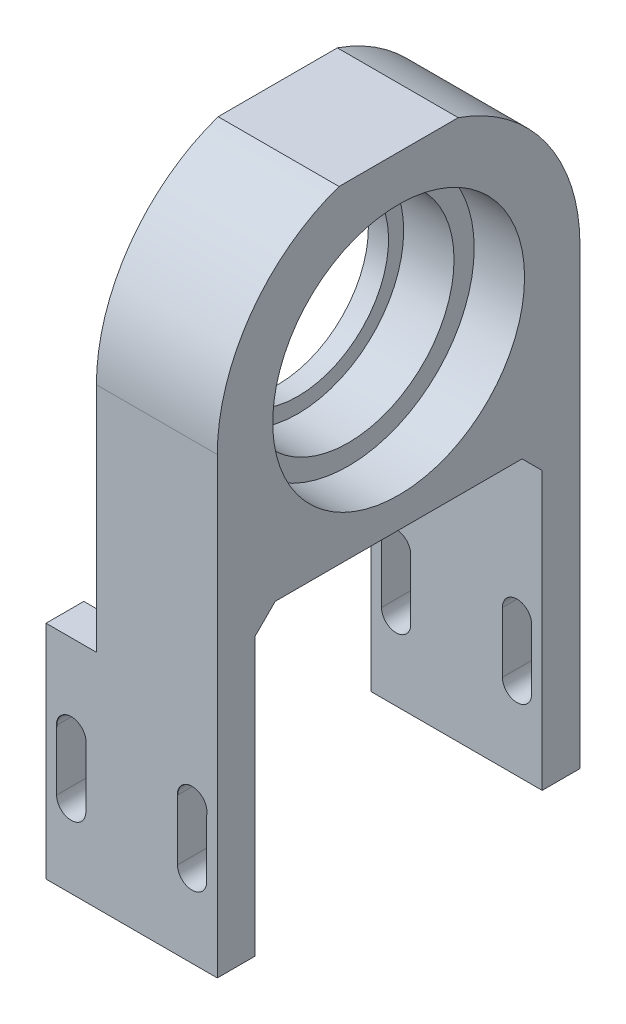
SolidWorks part; units mm, degrees
material "6061 Alloy"
ref_plane "Front Plane" through (0, 0, 0) normal (0, 0, 1) x (1, 0, 0)
ref_plane "Top Plane" through (0, 0, 0) normal (0, 1, 0) x (1, 0, 0)
ref_plane "Right Plane" through (0, 0, 0) normal (1, 0, 0) x (0, 0, -1)
sketch "Sketch1" plane through (0, 0, 0) normal (0, 0, 1) x (1, 0, 0)
  line L0 (0, 0) -> (17, 0)
  line L1 (17, 0) -> (17, 29)
  line L3 (17, 29) -> (17, 62)
  line L4 (17, 62) -> (5, 62)
  line L5 (5, 62) -> (5, 22)
  line L6 (5, 22) -> (0, 22)
  line L7 (0, 22) -> (0, 0)
  dimension "D1" = 17
  dimension "D2" = 62
  dimension "D3" = 22
  dimension "D4" = 12
extrude "Boss-Extrude1" add sketch "Sketch1" along normal blind 36
sketch "Sketch2" plane through (17, 0, 0) normal (1, 0, 0) x (0, 0, -1)
  line L0 (-18, 62) -> (-18, 12.1467) construction
  line L1 (-36, 62) -> (0, 62) construction
  circle A0 centre (-18, 45) radius 10.5
  dimension "D1" = 21
  dimension "D2" = 17
extrude "Cut-Extrude1" cut sketch "Sketch2" against normal through all
sketch "Sketch3" plane through (17, 0, 0) normal (1, 0, 0) x (0, 0, -1)
  line L0 (-36, 0) -> (0, 0) construction
  line L1 (-32.25, 0) -> (-3.75, 0)
  line L2 (-32.25, 0) -> (-32.25, 29.5)
  line L3 (-32.25, 29.5) -> (-3.75, 29.5)
  line L4 (-3.75, 0) -> (-3.75, 29.5)
  line L6 (-18, 0) -> (-18, 45) construction
  dimension "D1" = 28.5
  dimension "D2" = 29.5
extrude "Cut-Extrude2" cut sketch "Sketch3" against normal through all
chamfer "Chamfer1" distance 2 angle 45 2 edges at (11, 29.5, 32.25) (11, 29.5, 3.75)
sketch "Sketch6" plane through (5, 0, 0) normal (-1, 0, 0) x (0, 0, 1)
  circle A0 centre (18, 45) radius 10.5 construction
  circle A1 centre (18, 45) radius 10.5
  circle A2 centre (18, 45) radius 9
  dimension "D1" = 1.5
extrude "Boss-Extrude2" add sketch "Sketch6" against normal blind 2
sketch "Sketch10" plane through (5, 0, 0) normal (-1, 0, 0) x (0, 0, 1)
  circle A0 centre (18, 45) radius 11
  circle A1 centre (18, 45) radius 15
  dimension "D1" = 22
  dimension "D2" = 30
extrude "Cut-Extrude4" cut sketch "Sketch10" against normal blind 0.6
sketch "Sketch11" plane through (17, 0, 0) normal (1, 0, 0) x (0, 0, -1)
  circle A0 centre (-18, 45) radius 12.5
  dimension "D1" = 25
extrude "Cut-Extrude5" cut sketch "Sketch11" against normal blind 5
sketch "Sketch14" plane through (0, 0, 36) normal (0, 0, 1) x (1, 0, 0)
  line L0 (2.5, 13.75) -> (14.5, 13.75)
  line L3 (8.5, 13.75) -> (8.5, 0)
  line L4 (0, 0) -> (17, 0) construction
  line L5 (5, 29.5) -> (17, 29.5) construction
  point P0 (14.5, 13.75)
  point P2 (2.5, 13.75)
  dimension "D1" = 15.75
  dimension "D2" = 12
hole_wizard "M2.5 Clearance Hole1" positions "Sketch14" profile "Sketch13" hole size "M2.5" standard "DIN" end condition through all
sketch "Sketch13" plane through (14.5, 13.75, 36) normal (1, 0, 0) x (0, -1, 0)
  line L0 (0, 0) -> (0, 36)
  line L1 (0, 36) -> (1.45, 36)
  line L2 (1.45, 36) -> (1.45, 0.025)
  line L3 (1.45, 0.025) -> (1.475, 0)
  line L5 (1.475, 0) -> (0, 0)
  line L6 (-1.45, 0.025) -> (-1.475, 0) construction
  line L11 (0, -6.35) -> (0, 107.95) construction
  dimension "Thru Hole Dia." = 2.9
  dimension "Thru Hole Depth" = 36
  dimension "Near C'Sink Dia." = 2.95
  dimension "Near C'Sink Angle" = 90
sketch "Sketch15" plane through (0, 0, 0) normal (0, 0, -1) x (-1, 0, 0)
  line L0 (-14.5, 13.75) -> (-14.5, 7.75) construction
  line L1 (-13.05, 13.75) -> (-13.05, 7.75)
  line L2 (-15.95, 13.75) -> (-15.95, 7.75)
  line L3 (-2.5, 13.75) -> (-2.5, 7.75) construction
  line L4 (-1.05, 13.75) -> (-1.05, 7.75)
  line L5 (-3.95, 13.75) -> (-3.95, 7.75)
  arc A0 (-13.05, 13.75) -> (-15.95, 13.75) centre (-14.5, 13.75) ccw
  arc A1 (-15.95, 7.75) -> (-13.05, 7.75) centre (-14.5, 7.75) ccw
  arc A2 (-1.05, 13.75) -> (-3.95, 13.75) centre (-2.5, 13.75) ccw
  arc A3 (-3.95, 7.75) -> (-1.05, 7.75) centre (-2.5, 7.75) ccw
  circle A4 centre (-14.5, 13.75) radius 1.45 construction
  point P3 (-14.5, 10.75)
  point P8 (-2.5, 10.75)
  dimension "D1" = 6
extrude "Cut-Extrude6" cut sketch "Sketch15" against normal through all
sketch "Sketch16" plane through (0, 0, 0) normal (0, 0, -1) x (-1, 0, 0)
  line L0 (0, 22) -> (-5, 32)
  line L1 (-5, 62) -> (-5, 22) construction
  dimension "D1" = 10
rib "Rib6" [suppressed] sketch "Sketch16" sketch "Sketch16" thickness 3.75 extrusion direction parallel to sketch draft on no parameters "D1"=3.75
sketch "Sketch17" plane through (17, 0, 0) normal (1, 0, 0) x (0, 0, -1)
  line L1 (-36, 62) -> (0, 62)
  line L2 (-36, 62) -> (-36, 45)
  line L3 (-36, 45) -> (0, 45)
  line L4 (0, 62) -> (0, 45)
  circle A0 centre (-18, 45) radius 18
  line M9 (0, 0) -> (0, 62)
  line M10 (0, 62) -> (-36, 62)
  line M11 (-36, 62) -> (-36, 0)
extrude "Cut-Extrude7" cut sketch "Sketch17" against normal through all contours A0 M10 M11 | A0 M9 M10
